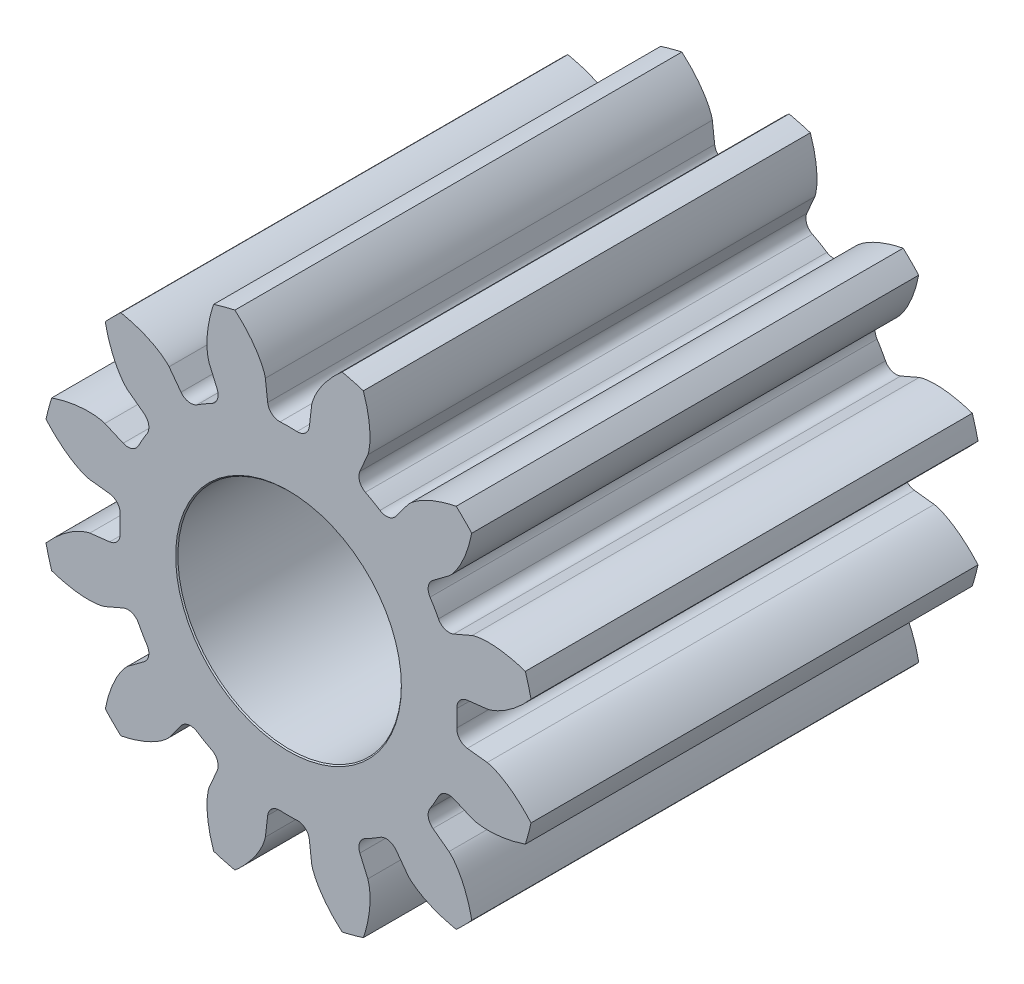
SolidWorks part; units mm, degrees
ref_plane "Front Plane" through (0, 0, 0) normal (0, 0, 1) x (1, 0, 0)
ref_plane "Top Plane" through (0, 0, 0) normal (0, 1, 0) x (1, 0, 0)
ref_plane "Right Plane" through (0, 0, 0) normal (1, 0, 0) x (0, 0, -1)
sketch "Sketch1" plane through (0, 0, 0) normal (0, 0, 1) x (1, 0, 0)
  line L0 (0, 0) -> (0, 4.7625) construction
  line L1 (-1.5306, 5.3196) -> (1.5306, 4.2054) construction
  circle A0 centre (0, 0) radius 3.7703 construction
  circle A1 centre (0, 0) radius 5.5562 construction
  circle A2 centre (0, 0) radius 4.7625 construction
  circle A3 centre (0, 0) radius 4.4753 construction
  point P8 (406.4, 0)
  point P13 (152.4, 0)
  dimension "OD | Outside Diameter" = 11.1125
  dimension "Root Diameter" = 7.5406
  dimension "Gear Pitch Diameter" = 9.525
  dimension "Base Diameter" = 8.9506
  dimension "Pressure Angle" = 20
  dimension "Number of Teeth" = 304.8
  dimension "Gear Pitch | Diametral Pitch" = 812.8
sketch "Sketch2" plane through (0, 0, 0) normal (1, 0, 0) x (0, 0, -1)
  line L0 (-5, 0) -> (5, 0) construction
  point P2 (0.5562, 0)
  point P5 (3.3344, 0)
  point P6 (-0.5562, 0)
  dimension "Length" = 10
  dimension "D1" = 5.5562
  dimension "D2" = 8.3344
  dimension "D3" = 5.5562
sketch "Sketch3" plane through (0, 0, 0) normal (0, 0, 1) x (1, 0, 0)
  circle A0 centre (0, 0) radius 5.5562
  circle A1 centre (0, 0) radius 5.5562 construction
extrude "Boss-Extrude1" add sketch "Sketch3" against normal up to vertex (5 mm away) and the other way up to vertex (5 mm away) up to point (0, 0, -5) other way up to point (0, 0, 5)
sketch "Sketch4" plane through (0, 0, 0) normal (0, 0, 1) x (1, 0, 0)
  line L0 (0, 0) -> (3.745, 0.4364) construction
  line L2 (0, 0) -> (3.745, -0.4364) construction
  line L4 (3.745, 0.4364) -> (4.4452, 0.5179)
  line L5 (4.4452, -0.5179) -> (3.745, -0.4364)
  arc A0 (3.745, 0.4364) -> (3.745, -0.4364) centre (0, 0) cw
  arc A3 (5.4254, 1.1987) -> (5.4254, -1.1987) centre (0, 0) cw
  circle A4 centre (0, 0) radius 5.5562 construction
  spline S0 degree 4 poles (4.4452, 0.5179) (4.447, 0.5182) (4.452, 0.5189) (4.4613, 0.5207) (4.4765, 0.524) (4.4957, 0.5289) (4.5203, 0.5361) (4.5491, 0.5456) (4.5805, 0.5571) (4.6143, 0.5707) (4.6477, 0.5853) (4.6807, 0.6008) (4.7133, 0.6171) (4.7525, 0.6378) (4.799, 0.6639) (4.8525, 0.6964) (4.9122, 0.7355) (4.9721, 0.7778) (5.03, 0.8214) (5.0874, 0.8676) (5.1422, 0.9139) (5.1978, 0.9642) (5.2486, 1.0117) (5.304, 1.0674) (5.3484, 1.113) (5.4053, 1.1756) (5.4385, 1.2134) (5.4767, 1.2584) (5.4934, 1.2789) (5.5037, 1.2914) knots 0 0 0 0 0 0.005377 0.015084 0.028532 0.04661 0.064855 0.092111 0.119476 0.146842 0.174209 0.201575 0.228941 0.256307 0.307035 0.361767 0.4165 0.471232 0.525964 0.580697 0.635429 0.690161 0.744894 0.799626 0.854358 0.909091 0.954545 1 1 1 1 1 construction
  spline S1 degree 4 poles (4.4452, 0.5179) (4.447, 0.5182) (4.452, 0.5189) (4.4613, 0.5207) (4.4765, 0.524) (4.4957, 0.5289) (4.5203, 0.5361) (4.5491, 0.5456) (4.5805, 0.5571) (4.6143, 0.5707) (4.6477, 0.5853) (4.6807, 0.6008) (4.7133, 0.6171) (4.7525, 0.6378) (4.799, 0.6639) (4.8525, 0.6964) (4.9122, 0.7355) (4.9721, 0.7778) (5.03, 0.8214) (5.0874, 0.8676) (5.1422, 0.9139) (5.1978, 0.9642) (5.2486, 1.0117) (5.304, 1.0674) (5.3484, 1.113) (5.393, 1.1621) (5.4145, 1.1862) (5.4254, 1.1987) knots 0 0 0 0 0 0.005377 0.015084 0.028532 0.04661 0.064855 0.092111 0.119476 0.146842 0.174209 0.201575 0.228941 0.256307 0.307035 0.361767 0.4165 0.471232 0.525964 0.580697 0.635429 0.690161 0.744894 0.799626 0.854358 0.909091 0.909091 0.909091 0.909091 0.909091
  spline S2 degree 4 poles (4.4452, -0.5179) (4.447, -0.5182) (4.452, -0.5189) (4.4613, -0.5207) (4.4765, -0.524) (4.4957, -0.5289) (4.5203, -0.5361) (4.5491, -0.5456) (4.5805, -0.5571) (4.6143, -0.5707) (4.6477, -0.5853) (4.6807, -0.6008) (4.7133, -0.6171) (4.7525, -0.6378) (4.799, -0.6639) (4.8525, -0.6964) (4.9122, -0.7355) (4.9721, -0.7778) (5.03, -0.8214) (5.0874, -0.8676) (5.1422, -0.9139) (5.1978, -0.9642) (5.2486, -1.0117) (5.304, -1.0674) (5.3484, -1.113) (5.4053, -1.1756) (5.4385, -1.2134) (5.4767, -1.2584) (5.4934, -1.2789) (5.5037, -1.2914) knots 0 0 0 0 0 0.005377 0.015084 0.028532 0.04661 0.064855 0.092111 0.119476 0.146842 0.174209 0.201575 0.228941 0.256307 0.307035 0.361767 0.4165 0.471232 0.525964 0.580697 0.635429 0.690161 0.744894 0.799626 0.854358 0.909091 0.954545 1 1 1 1 1 construction
  spline S3 degree 4 poles (4.4452, -0.5179) (4.447, -0.5182) (4.452, -0.5189) (4.4613, -0.5207) (4.4765, -0.524) (4.4957, -0.5289) (4.5203, -0.5361) (4.5491, -0.5456) (4.5805, -0.5571) (4.6143, -0.5707) (4.6477, -0.5853) (4.6807, -0.6008) (4.7133, -0.6171) (4.7525, -0.6378) (4.799, -0.6639) (4.8525, -0.6964) (4.9122, -0.7355) (4.9721, -0.7778) (5.03, -0.8214) (5.0874, -0.8676) (5.1422, -0.9139) (5.1978, -0.9642) (5.2486, -1.0117) (5.304, -1.0674) (5.3484, -1.113) (5.393, -1.1621) (5.4145, -1.1862) (5.4254, -1.1987) knots 0 0 0 0 0 0.005377 0.015084 0.028532 0.04661 0.064855 0.092111 0.119476 0.146842 0.174209 0.201575 0.228941 0.256307 0.307035 0.361767 0.4165 0.471232 0.525964 0.580697 0.635429 0.690161 0.744894 0.799626 0.854358 0.909091 0.909091 0.909091 0.909091 0.909091
  dimension "D1" = 7.5406
extrude "Cut-Extrude1" cut sketch "Sketch4" against normal through all both and the other way through all
fillet "Fillet1" radius 0.2663 2 edges at (3.745, -0.4364, 0) (3.745, 0.4364, 0)
pattern_circular "CirPattern1" count 12 over 360 about axis through (0, 0, 5) along (0, 0, -1) of "Cut-Extrude1", "Fillet1"
sketch "Sketch5" plane through (0, 0, 5) normal (0, 0, 1) x (1, 0, 0)
  point P0 (0, 0)
hole_wizard "Ø5.0mm Dowel Hole1" positions "Sketch5" profile "Sketch6" hole size "Ø5.0" standard "ANSI Metric" end condition through all
sketch "Sketch6" plane through (0, 0, 5) normal (1, 0, 0) x (0, -1, 0)
  line L0 (0, 0) -> (0, 10)
  line L1 (0, 10) -> (2.5, 10)
  line L2 (2.5, 10) -> (2.5, 0.025)
  line L3 (2.5, 0.025) -> (2.525, 0)
  line L5 (2.525, 0) -> (0, 0)
  line L6 (-2.5, 0.025) -> (-2.525, 0) construction
  line L11 (0, -6.35) -> (0, 107.95) construction
  dimension "Thru Hole Dia." = 5
  dimension "Thru Hole Depth" = 10
  dimension "Near C'Sink Dia." = 5.05
  dimension "Near C'Sink Angle" = 90
equation "\"Root Diameter@Sketch1\"=\"Root Diameter\""
equation "\"OD | Outside Diameter@Sketch1\"=\"Outside Diameter\""
equation "\"D1@CirPattern1\"=\"Number of Teeth\""
equation "\"Diametral Pitch\"=32"
equation "\"Number of Teeth\"=12"
equation "\"Pressure Angle\"=20"
equation "\"Pitch Diameter\"= \"Number of Teeth\" / \"Diametral Pitch\""
equation "\"Base Diameter\"= \"Pitch Diameter\" * cos ( \"Pressure Angle\" )"
equation "\"Outside Diameter\"= ( \"Number of Teeth\" + 2 ) / \"Diametral Pitch\""
equation "\"Dedendum\"= 1.25 / \"Diametral Pitch\""
equation "\"Root Diameter\"= \"Pitch Diameter\" - ( 2 * \"Dedendum\" )"
equation "\"Pitch Angle\"= 360deg / \"Number of Teeth\""
equation "\"Alpha\"= sqr ( \"Pitch Diameter\" ^ 2 - \"Base Diameter\" ^ 2 ) / \"Base Diameter\" * 180 / PI - \"Pressure Angle\""
equation "\"Beta\"= ( \"Pitch Angle\" / 4 - \"Alpha\" )"
equation "\"Phi\"= sqr ( ( \"Outside Diameter\" / 2 ) ^ 2 - ( \"Base Diameter\" / 2 ) ^ 2 ) / ( \"Base Diameter\" / 2 )"
equation "\"Addendum\"= 1 / \"Diametral Pitch\""
equation "\"WorkingDepth\"= 2 / \"Diametral Pitch\""
equation "\"WholeDepth\"= 2.25 / \"Diametral Pitch\""
equation "\"Clearance\"= 0.25 / \"Diametral Pitch\""
equation "\"ToothThickness\"= ( pi * 2 ) / \"Diametral Pitch\""
equation "\"CircularPitch\"= pi / \"Diametral Pitch\""
equation "\"Number of Teeth@Sketch1\"=\"Number of Teeth\""
equation "\"Gear Pitch | Diametral Pitch@Sketch1\"=\"Diametral Pitch\""
equation "\"Pressure Angle@Sketch1\"=\"Pressure Angle\""
equation "\"Gear Pitch Diameter@Sketch1\"=\"Pitch Diameter\""
equation "\"Base Diameter@Sketch1\"=\"Base Diameter\""
equation "\"Fillet\"= \"Clearance\" * cos ( \"Pressure Angle\" ) * tan ( ( 90 + \"Pressure Angle\" ) / 2 )"
equation "\"D1@Fillet1\"=\"Fillet\""
equation "\"D1@Sketch4\"=if( \"Base Diameter\">\"Root Diameter\",\"Root Diameter\",\"Base Diameter\"-.00001)"
equation "\"D1@Sketch2\"=\"OD | Outside Diameter@Sketch1\"*2*0.5*0.5"
equation "\"D2@Sketch2\"=\"D1@Sketch2\"*1.5"
equation "\"D3@Sketch2\"=\"D1@Sketch2\""
equation "\"Length\"= 1cm"
equation "\"Length@Sketch2\"= \"Length\""
